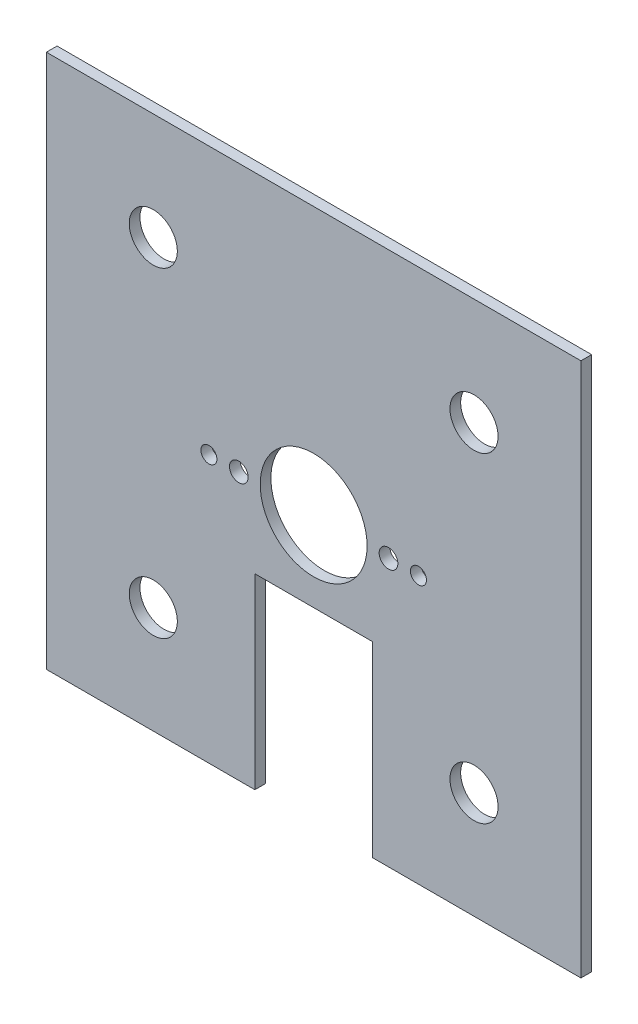
SolidWorks part; units mm, degrees
ref_plane "Front Plane" through (0, 0, 0) normal (0, 0, 1) x (1, 0, 0)
ref_plane "Top Plane" through (0, 0, 0) normal (0, 1, 0) x (1, 0, 0)
ref_plane "Right Plane" through (0, 0, 0) normal (1, 0, 0) x (0, 0, -1)
sketch "Sketch1" plane through (0, 0, 0) normal (0, 0, 1) x (1, 0, 0)
  line L0 (-9.8, 0) -> (9.8, 0) construction
  line L1 (-25, -25) -> (-5.5, -25)
  line L2 (-25, -25) -> (-25, 25)
  line L3 (-25, 25) -> (25, 25)
  line L4 (25, -25) -> (25, 25)
  line L5 (-25, -25) -> (25, 25) construction
  line L6 (-25, 25) -> (25, -25) construction
  line L7 (0, 0) -> (0, -7.5) construction
  line L8 (-5.5, -7.5) -> (5.5, -7.5)
  line L9 (5.5, -7.5) -> (5.5, -25)
  line L10 (-5.5, -7.5) -> (-5.5, -25)
  line L11 (0, -25) -> (25, -25)
  circle A0 centre (-15, 15) radius 2.25
  circle A1 centre (15, 15) radius 2.25
  circle A2 centre (15, -15) radius 2.25
  circle A3 centre (-15, -15) radius 2.25
  circle A4 centre (0, 0) radius 5
  circle A5 centre (7, 0) radius 0.875
  circle A6 centre (9.8, 0) radius 0.75
  circle A7 centre (-7, 0) radius 0.875
  circle A8 centre (-9.8, 0) radius 0.75
  point P0 (0, 0)
  point P32 (0, -7.5)
  dimension "D6" = 4.5
  dimension "D7" = 10
  dimension "D8" = 1.75
  dimension "D9" = 1.5
  dimension "D2" = 15
  dimension "D3" = 15
  dimension "D4" = 15
  dimension "D5" = 15
  dimension "D10" = 7
  dimension "D11" = 9.8
  dimension "D12" = 19.6
  dimension "D13" = 14
  dimension "D14" = 11
  dimension "D15" = 7.5
  dimension "D16" = 10
extrude "Boss-Extrude1" add sketch "Sketch1" along normal blind 1 contours L9 L11 L4 L3 L2 L1 L10 L8 A8 A7 A6 A5 A4 A3 A2 A1 A0
fillet "Fillet1" [suppressed] radius 10
fillet "Fillet2" [suppressed] radius 10
fillet "Fillet3" [suppressed] radius 10
fillet "Fillet4" [suppressed] radius 10
fillet "Fillet5" [suppressed] radius 10
fillet "Fillet6" [suppressed] radius 10
fillet "Fillet7" [suppressed] radius 1
fillet "Fillet8" [suppressed] radius 1
